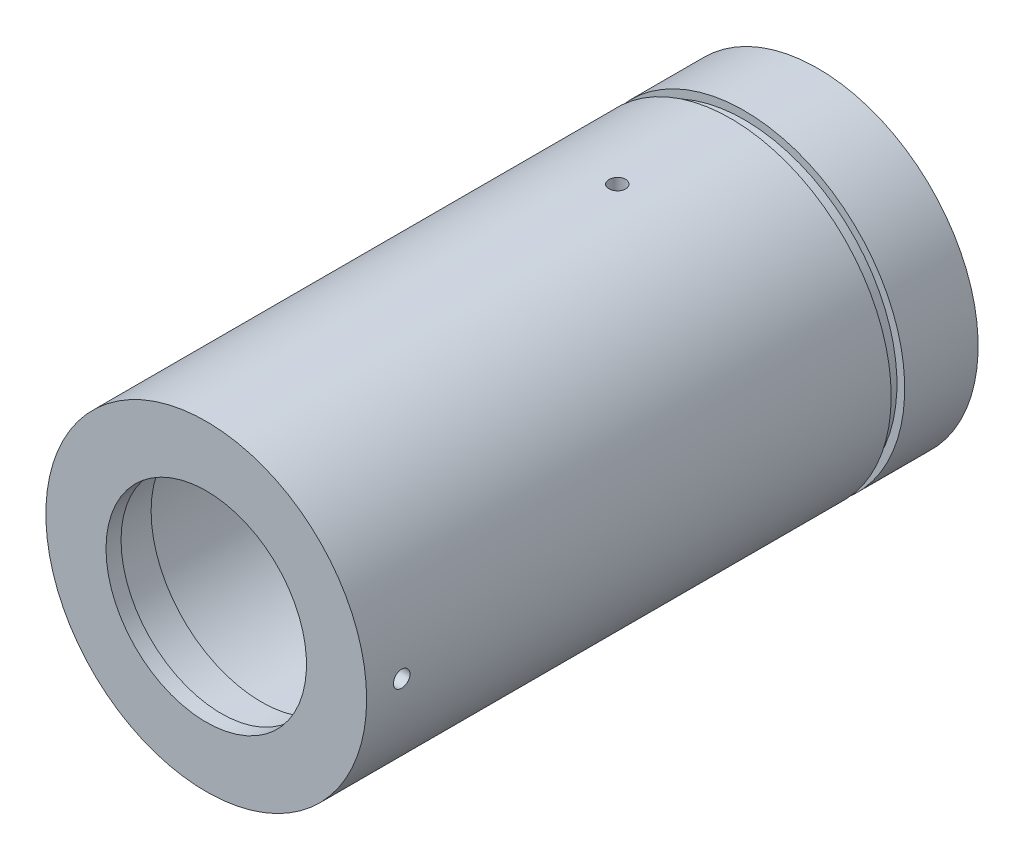
SolidWorks part; units mm, degrees
ref_plane "Front Plane" through (0, 0, 0) normal (0, 0, 1) x (1, 0, 0)
ref_plane "Top Plane" through (0, 0, 0) normal (0, 1, 0) x (1, 0, 0)
ref_plane "Right Plane" through (0, 0, 0) normal (1, 0, 0) x (0, 0, -1)
sketch "Sketch1" plane through (0, 0, 0) normal (0, 0, 1) x (1, 0, 0)
  circle A0 centre (0, 0) radius 32
extrude "Body" add sketch "Sketch1" along normal blind 122
sketch "Sketch2" plane through (0, 0, 0) normal (0, 0, 1) x (1, 0, 0)
  circle A0 centre (0, 0) radius 20
extrude "Lip_bore" cut sketch "Sketch2" along normal blind 122
sketch "Sketch3" plane through (0, 0, 0) normal (0, 0, 1) x (1, 0, 0)
  circle A0 centre (0, 0) radius 22
extrude "Bridge_seat" cut sketch "Sketch3" along normal blind 119
sketch "Sketch4" plane through (0, 0, 0) normal (0, 0, 1) x (1, 0, 0)
  circle A0 centre (0, 0) radius 25
extrude "Hopper" cut sketch "Sketch4" along normal blind 111
sketch "Sketch5" plane through (0, 0, 0) normal (0, 0, 1) x (1, 0, 0)
  circle A0 centre (0, 0) radius 27
extrude "Burr_seat" cut sketch "Sketch5" along normal blind 50
sketch "Sketch6" plane through (0, 0, 0) normal (0, 0, 1) x (1, 0, 0)
  circle A0 centre (0, 0) radius 28
extrude "Pilot_seat" cut sketch "Sketch6" along normal blind 30
sketch "Sketch7" plane through (0, 0, 0) normal (0, 0, 1) x (1, 0, 0)
  circle A0 centre (0, 0) radius 28.46
extrude "Thread_minor" cut sketch "Sketch7" along normal blind 10
ref_plane "Plane_z10" through (0, 0, 10) normal (0, 0, 1) x (1, 0, 0)
sketch "Sketch8" plane through (0, 0, 10) normal (0, 0, 1) x (1, 0, 0)
  circle A0 centre (0, 0) radius 29.5
extrude "Thread_relief" cut sketch "Sketch8" along normal blind 2
ref_plane "Plane_z14_65" through (0, 0, 14.65) normal (0, 0, 1) x (1, 0, 0)
sketch "Sketch9" plane through (0, 0, 14.65) normal (0, 0, 1) x (1, 0, 0)
  circle A0 centre (0, 0) radius 33
  circle A1 centre (0, 0) radius 30.45
extrude "Oring_groove" cut sketch "Sketch9" along normal blind 2.7
ref_plane "Plane_y26_5" through (0, 26.5, 0) normal (0, 1, 0) x (1, 0, 0)
sketch "Sketch10" plane through (0, 26.5, 0) normal (0, 1, 0) x (1, 0, 0)
  circle A0 centre (0, -40) radius 1.65
extrude "Burr_screw_90" cut sketch "Sketch10" along normal blind 6
ref_plane "Plane_ym32_5" through (0, -32.5, 0) normal (0, 1, 0) x (1, 0, 0)
sketch "Sketch11" plane through (0, -32.5, 0) normal (0, 1, 0) x (1, 0, 0)
  circle A0 centre (0, -40) radius 1.65
extrude "Burr_screw_270" cut sketch "Sketch11" along normal blind 6
ref_plane "Plane_x21_5" through (21.5, 0, 0) normal (1, 0, 0) x (0, 0, -1)
sketch "Sketch12" plane through (21.5, 0, 0) normal (1, 0, 0) x (0, 0, -1)
  circle A0 centre (-115, 0) radius 1.65
extrude "Bridge_screw" cut sketch "Sketch12" along normal blind 11
ref_plane "Plane_xm32_5" through (-32.5, 0, 0) normal (1, 0, 0) x (0, 0, -1)
sketch "Sketch13" plane through (-32.5, 0, 0) normal (1, 0, 0) x (0, 0, -1)
  circle A0 centre (-22, 0) radius 2.5
extrude "Plunger_hole" cut sketch "Sketch13" along normal blind 5
